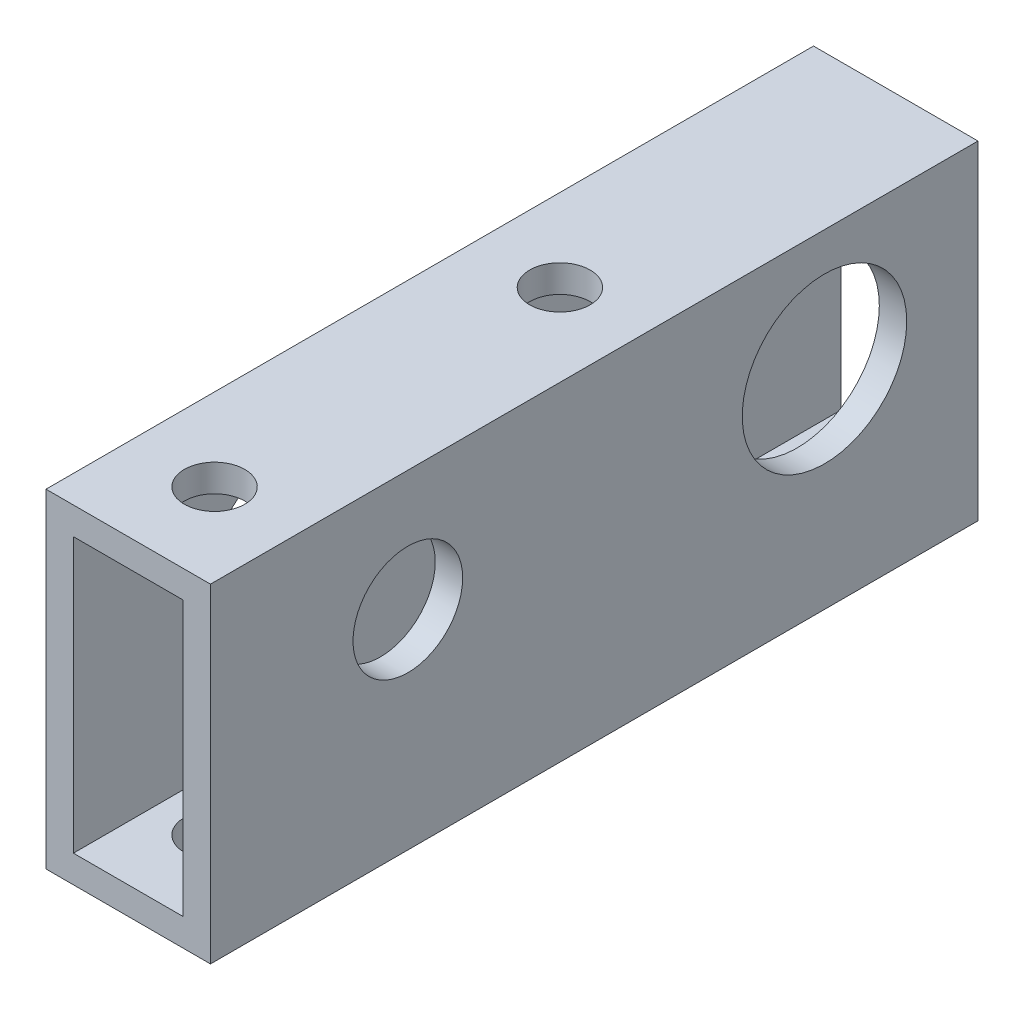
SolidWorks part; units mm, degrees
ref_plane "Front Plane" through (0, 0, 0) normal (0, 0, 1) x (1, 0, 0)
ref_plane "Top Plane" through (0, 0, 0) normal (0, 1, 0) x (1, 0, 0)
ref_plane "Right Plane" through (0, 0, 0) normal (1, 0, 0) x (0, 0, -1)
sketch "Sketch1" plane through (0, 0, 0) normal (0, 0, 1) x (1, 0, 0)
  line L1 (-6.35, -15.875) -> (6.35, -15.875)
  line L2 (-6.35, -15.875) -> (-6.35, 15.875)
  line L3 (-6.35, 15.875) -> (6.35, 15.875)
  line L4 (6.35, -15.875) -> (6.35, 15.875)
  line L5 (-6.35, -15.875) -> (6.35, 15.875) construction
  line L6 (-6.35, 15.875) -> (6.35, -15.875) construction
  line L7 (-9.525, -19.05) -> (9.525, -19.05)
  line L8 (-9.525, -19.05) -> (-9.525, 19.05)
  line L9 (-9.525, 19.05) -> (9.525, 19.05)
  line L10 (9.525, -19.05) -> (9.525, 19.05)
  line L11 (-9.525, -19.05) -> (9.525, 19.05) construction
  line L12 (-9.525, 19.05) -> (9.525, -19.05) construction
  point P0 (0, 0)
  point P5 (0, 0)
  dimension "D1" = 19.05
  dimension "D2" = 38.1
  dimension "D3" = 3.175
  dimension "D4" = 3.175
extrude "Boss-Extrude1" add sketch "Sketch1" along normal mid plane 88.9
sketch "Sketch2" plane through (0, -19.05, 0) normal (0, -1, 0) x (1, 0, 0)
  line L0 (-9.525, 44.45) -> (9.525, 44.45) construction
  circle A0 centre (0, 34.45) radius 3.5
  circle A1 centre (0, -5.55) radius 3.5
  dimension "D1" = 7
  dimension "D2" = 10
  dimension "D3" = 40
extrude "Cut-Extrude1" cut sketch "Sketch2" against normal blind 76.2
sketch "Sketch3" plane through (9.525, 0, 0) normal (1, 0, 0) x (0, 0, -1)
  line L0 (-44.45, 19.05) -> (44.45, 19.05) construction
  line L1 (-44.45, -19.05) -> (-44.45, 19.05) construction
  line L2 (44.45, -19.05) -> (44.45, 19.05) construction
  circle A0 centre (-21.59, 5.08) radius 6.35
  circle A1 centre (26.67, 5.08) radius 9.525
  dimension "D1" = 12.7
  dimension "D2" = 19.05
  dimension "D3" = 13.97
  dimension "D4" = 22.86
  dimension "D5" = 17.78
extrude "Cut-Extrude2" cut sketch "Sketch3" against normal through all
